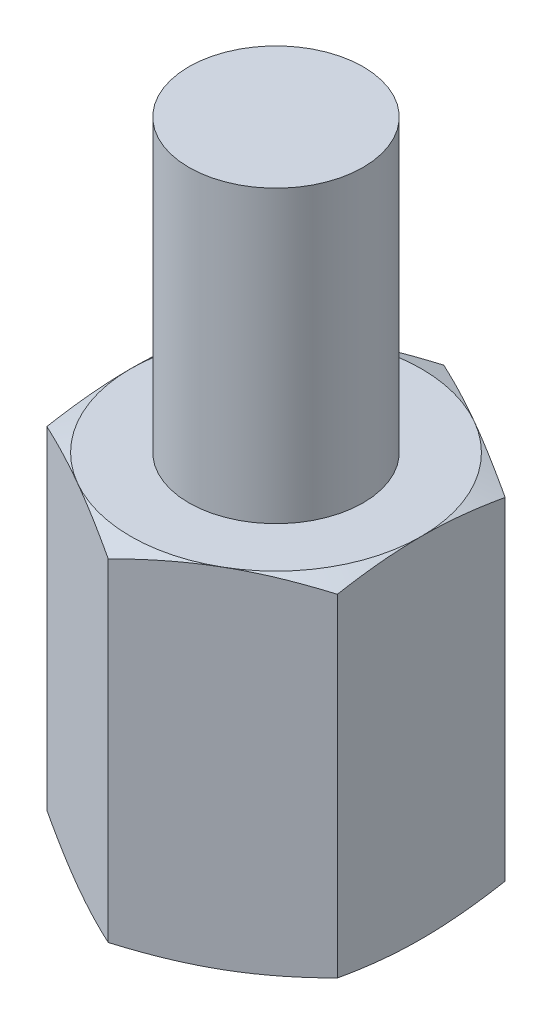
SolidWorks part; units mm, degrees
ref_plane "Front Plane" through (0, 0, 0) normal (0, 0, 1) x (1, 0, 0)
ref_plane "Top Plane" through (0, 0, 0) normal (0, 1, 0) x (1, 0, 0)
ref_plane "Right Plane" through (0, 0, 0) normal (1, 0, 0) x (0, 0, -1)
sketch "Sketch1" plane through (0, 0, 0) normal (0, 1, 0) x (1, 0, 0)
  line L1 (0, 2.8868) -> (-2.5, 1.4434)
  line L2 (-2.5, 1.4434) -> (-2.5, -1.4434)
  line L3 (-2.5, -1.4434) -> (0, -2.8868)
  line L4 (0, -2.8868) -> (2.5, -1.4434)
  line L5 (2.5, -1.4434) -> (2.5, 1.4434)
  line L6 (2.5, 1.4434) -> (0, 2.8868)
  circle A0 centre (0, 0) radius 2.5 construction
  circle A1 centre (0, 0) radius 1.5
  point P1 (2.5, 0)
  dimension "D2" = 3
  dimension "D1" = 5
extrude "Boss-Extrude1" add sketch "Sketch1" along normal blind 6
sketch "Sketch3" plane through (0, 6, 0) normal (0, 1, 0) x (1, 0, 0)
  circle A0 centre (0, 0) radius 2.5
ref_plane "Plane1" through (0, 0, 0) normal (-1, 0, 0) x (0, 0, 1)
sketch "Sketch6" plane through (0, 0, 0) normal (-1, 0, 0) x (0, 0, 1)
  line L0 (2.5, 6) -> (2.8868, 6)
  line L1 (1.4434, 6) -> (2.8868, 6) construction
  line L2 (2.5, 6) -> (-2.5, 6) construction
  line L3 (2.8868, 6) -> (2.8868, 5.8592)
  line L4 (2.8868, 6) -> (2.8868, 0) construction
  line L5 (2.8868, 5.8592) -> (2.5, 6)
  line L6 (0, 6) -> (0, 43.573) construction
  dimension "D1" = 20
  dimension "D2" = 0.3868
revolve "Cut-Revolve1" cut sketch "Sketch6" angle 360 about L6
ref_plane "Plane2" through (0, 3, 0) normal (0, 1, 0) x (1, 0, 0)
mirror "Mirror1" about plane through (0, 3, 0) normal (0, 1, 0) of "Cut-Revolve1"
sketch "Sketch7" plane through (0, 6, 0) normal (0, 1, 0) x (1, 0, 0)
  circle A0 centre (0, 0) radius 1.5
extrude "Boss-Extrude2" add sketch "Sketch7" along normal blind 5 and the other way blind 1.5
